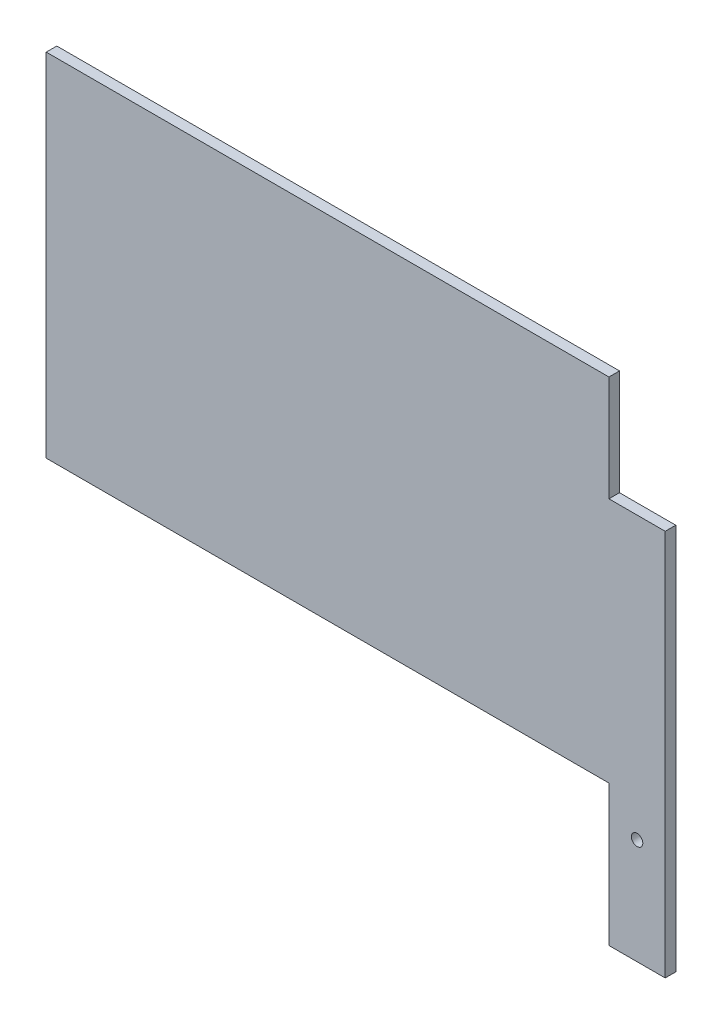
SolidWorks part; units mm, degrees
material "ABS"
ref_plane "Front Plane" through (0, 0, 0) normal (0, 0, 1) x (1, 0, 0)
ref_plane "Top Plane" through (0, 0, 0) normal (0, 1, 0) x (1, 0, 0)
ref_plane "Right Plane" through (0, 0, 0) normal (1, 0, 0) x (0, 0, -1)
sketch "Sketch1" plane through (0, 0, 0) normal (0, 0, 1) x (1, 0, 0)
  line L1 (-26.749, 19.5473) -> (53.251, 19.5473)
  line L2 (-26.749, 19.5473) -> (-26.749, -30.4527)
  line L3 (-26.749, -30.4527) -> (53.251, -30.4527)
  line L4 (53.251, 19.5473) -> (53.251, -30.4527)
  dimension "D1" = 80
  dimension "D2" = 50
extrude "Boss-Extrude1" add sketch "Sketch1" along normal blind 1.5
sketch "Sketch6" plane through (53.251, 0, 0) normal (1, 0, 0) x (0, 0, -1)
  line L0 (-1.5, 19.5473) -> (0, 19.5473) construction
  line L1 (-1.5, 4.5473) -> (0, 4.5473)
  line L2 (-1.5, 4.5473) -> (-1.5, -15.4527)
  line L3 (-1.5, -15.4527) -> (0, -15.4527)
  line L4 (0, 4.5473) -> (0, -15.4527)
  line L5 (-1.5, -30.4527) -> (0, -30.4527) construction
  line L6 (0, -30.4527) -> (0, 19.5473) construction
  line L7 (-1.5, -30.4527) -> (-1.5, 19.5473) construction
  dimension "D1" = 15
  dimension "D2" = 15
  dimension "D3" = 0
  dimension "D4" = 0
extrude "Boss-Extrude4" add sketch "Sketch6" along normal blind 8
sketch "Sketch7" plane through (0, -15.4527, 0) normal (0, -1, 0) x (1, 0, 0)
  circle A0 centre (19.1457, 1.5) radius 0.7944
sketch "Sketch8" plane through (0, -15.4527, 0) normal (0, -1, 0) x (1, 0, 0)
  line L1 (53.251, 1.5) -> (61.251, 1.5)
  line L2 (53.251, 1.5) -> (53.251, 0)
  line L3 (53.251, 0) -> (61.251, 0)
  line L4 (61.251, 1.5) -> (61.251, 0)
extrude "Boss-Extrude5" add sketch "Sketch8" along normal blind 35
sketch "Sketch9" plane through (0, 0, 0) normal (0, 0, -1) x (-1, 0, 0)
  line L0 (-57.251, 4.5473) -> (-57.251, -50.4527) construction
  line L1 (-61.251, 4.5473) -> (-53.251, 4.5473) construction
  line L2 (-53.251, -50.4527) -> (-61.251, -50.4527) construction
  line L3 (26.749, -30.4527) -> (-53.251, -30.4527) construction
  circle A0 centre (-57.251, -35.4527) radius 0.815
  dimension "D1" = 1.63
  dimension "D2" = 5
extrude "Cut-Extrude2" cut sketch "Sketch9" against normal through all
